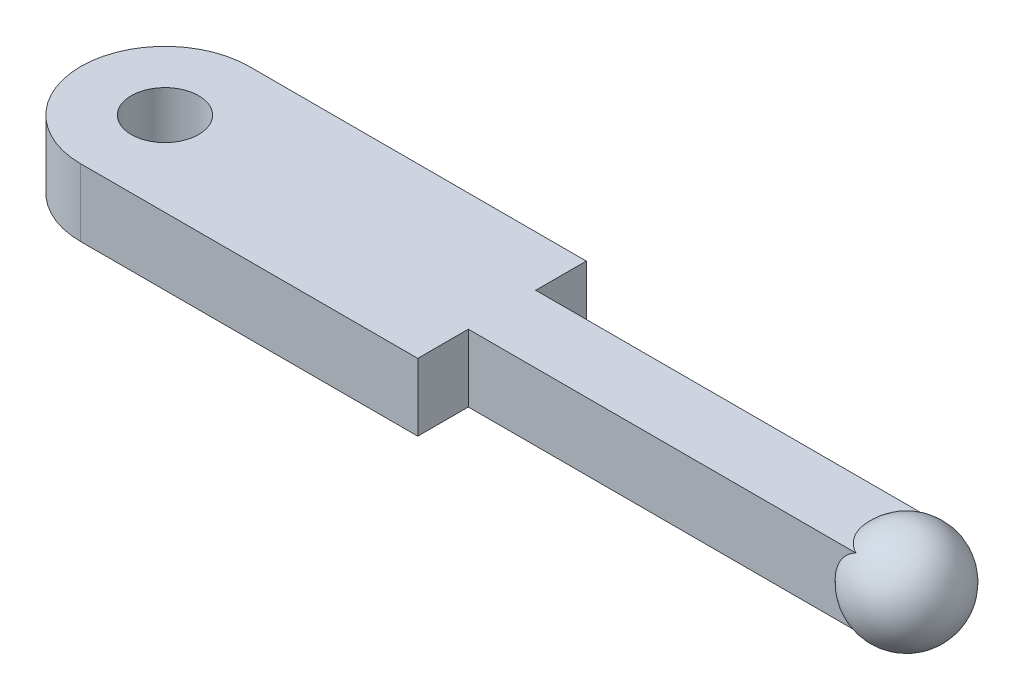
SolidWorks part; units mm, degrees
ref_plane "Front Plane" through (0, 0, 0) normal (0, 0, 1) x (1, 0, 0)
ref_plane "Top Plane" through (0, 0, 0) normal (0, 1, 0) x (1, 0, 0)
ref_plane "Right Plane" through (0, 0, 0) normal (1, 0, 0) x (0, 0, -1)
sketch "Sketch1" plane through (0, 0, 0) normal (0, 1, 0) x (1, 0, 0)
  line L0 (-10, 0) -> (0, 0) construction
  line L1 (-10, 2.5) -> (0, 2.5)
  line L2 (-10, -2.5) -> (0, -2.5)
  line L3 (0, 2.5) -> (0, -2.5)
  arc A0 (-10, 2.5) -> (-10, -2.5) centre (-10, 0) ccw
  circle A3 centre (-10, 0) radius 1
  point P3 (0, 0)
  dimension "D3" = 2
  dimension "D4" = 2.5
  dimension "D5" = 10
  dimension "D6" = 2.5
  dimension "D2" = 5
  dimension "D12" = 10
extrude "Boss-Extrude1" add sketch "Sketch1" along normal blind 2
sketch "Sketch2" plane through (0, 0, 0) normal (0, 0, 1) x (1, 0, 0)
  line L1 (0.0125, 0) -> (-0.0002, 0)
  line L5 (-10, 0) -> (0, 0) construction
  point P2 (0.0125, 1)
  dimension "D2" = 0
sketch "Sketch4" plane through (0, 0, 0) normal (1, 0, 0) x (0, 0, -1)
  line L1 (-1, 2) -> (1, 2)
  line L2 (-1, 2) -> (-1, 0)
  line L3 (-1, 0) -> (1, 0)
  line L4 (1, 2) -> (1, 0)
  line L5 (-1, 2) -> (1, 0) construction
  line L6 (-1, 0) -> (1, 2) construction
  point P0 (0, 1)
  dimension "D1" = 2
  dimension "D2" = 2
extrude "Boss-Extrude2" add sketch "Sketch4" along normal blind 12
ref_plane "Plane1" through (0, 0, 0) normal (0, 0, 1) x (1, 0, 0)
sketch "Sketch5" plane through (0, 0, 0) normal (0, 0, 1) x (1, 0, 0)
  line L0 (0.0125, 1) -> (12, 1) construction
  line L1 (12, 2) -> (12, 0) construction
  line L3 (10.6142, 1.574) -> (12, 1)
  line L4 (12, 1) -> (13.5, 1)
  arc A0 (13.5, 1) -> (10.6142, 1.574) centre (12, 1) ccw
  dimension "D1" = 1.5
  dimension "D2" = 157.5
revolve "Revolve1" add sketch "Sketch5" angle 360 about L0
